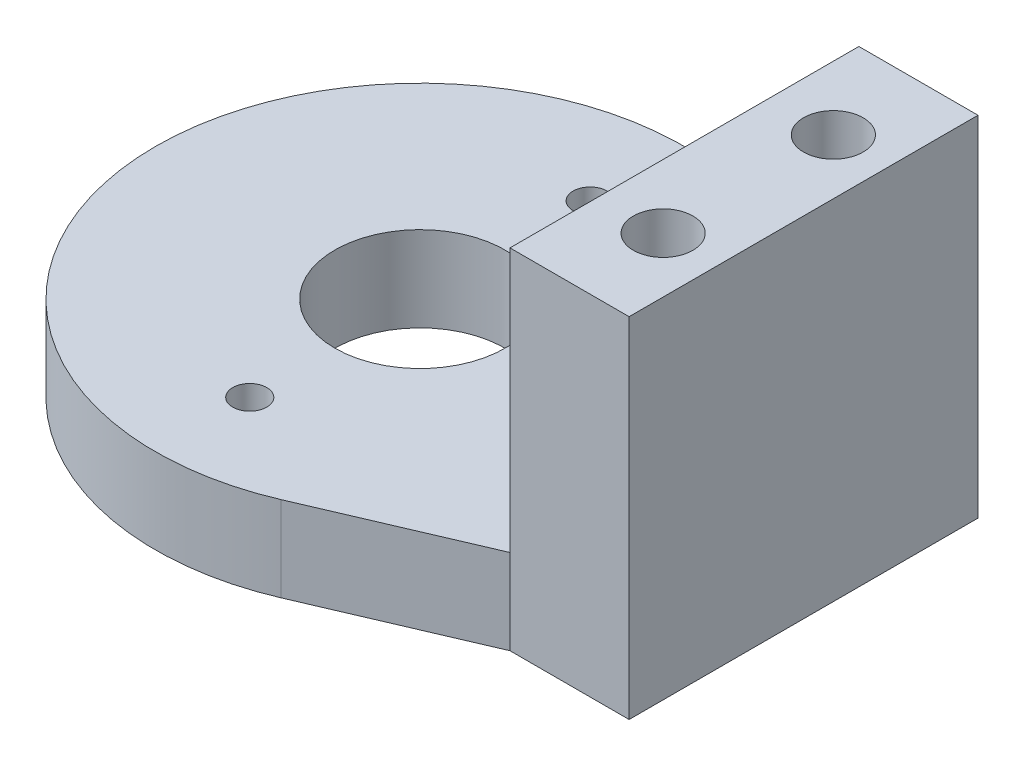
SolidWorks part; units mm, degrees
ref_plane "Front" through (0, 0, 0) normal (0, 0, 1) x (1, 0, 0)
ref_plane "Top" through (0, 0, 0) normal (0, 1, 0) x (1, 0, 0)
ref_plane "Right" through (0, 0, 0) normal (1, 0, 0) x (0, 0, -1)
sketch "Sketch1" plane through (0, 0, 0) normal (0, 1, 0) x (1, 0, 0)
  line L1 (0, 0) -> (7, 0)
  line L2 (0, 0) -> (0, -20.5)
  line L3 (0, -20.5) -> (7, -20.5)
  line L4 (7, 0) -> (7, -20.5)
  dimension "D1" = 7
  dimension "D2" = 20.5
extrude "mountingBase" add sketch "Sketch1" along normal blind 20.5003
sketch "Sketch2" plane through (0, 20.5003, 0) normal (0, 1, 0) x (1, 0, 0)
  line L0 (0, 0) -> (0, -20.5) construction
  line L1 (0, -10.25) -> (7, -10.25) construction
  line L2 (7, -20.5) -> (7, 0) construction
  line L3 (7, 0) -> (0, 0) construction
  circle A0 centre (3.75, -5.25) radius 1.75
  circle A1 centre (3.75, -15.25) radius 1.75
  dimension "D2" = 3.5
  dimension "D1" = 3.75
  dimension "D3" = 5.25
extrude "mountingHoles" cut sketch "Sketch2" against normal through all
sketch "Sketch3" plane through (0, 0, 0) normal (0, 1, 0) x (1, 0, 0)
  line L0 (0, 0) -> (0, -20.5) construction
  line L1 (0, 0) -> (-9.4224, 4.0351)
  line L2 (0, -20.5) -> (-9.4224, -24.5351)
  line L3 (0, 0) -> (0, -20.5)
  arc A0 (-9.4224, 4.0351) -> (-9.4224, -24.5351) centre (-15.5398, -10.25) ccw
  point P4 (0, -10.25)
  dimension "D1" = 15.5398
extrude "hornTab" add sketch "Sketch3" along normal blind 5
sketch "Sketch4" plane through (0, 5, 0) normal (0, 1, 0) x (1, 0, 0)
  line L0 (-15.5398, -10.25) -> (-31.0797, -10.25) construction
  circle A0 centre (-15.5398, -10.25) radius 15.5398 construction
  arc A1 (-9.4224, 4.0351) -> (-9.4224, -24.5351) centre (-15.5398, -10.25) ccw construction
  circle A2 centre (-15.5398, -0.25) radius 1
  circle A3 centre (-15.5398, -20.25) radius 1
  circle A4 centre (-15.5398, -10.25) radius 5
  dimension "D1" = 2
  dimension "D3" = 10
  dimension "D2" = 10
extrude "hornMountingHoles" cut sketch "Sketch4" against normal blind 5
